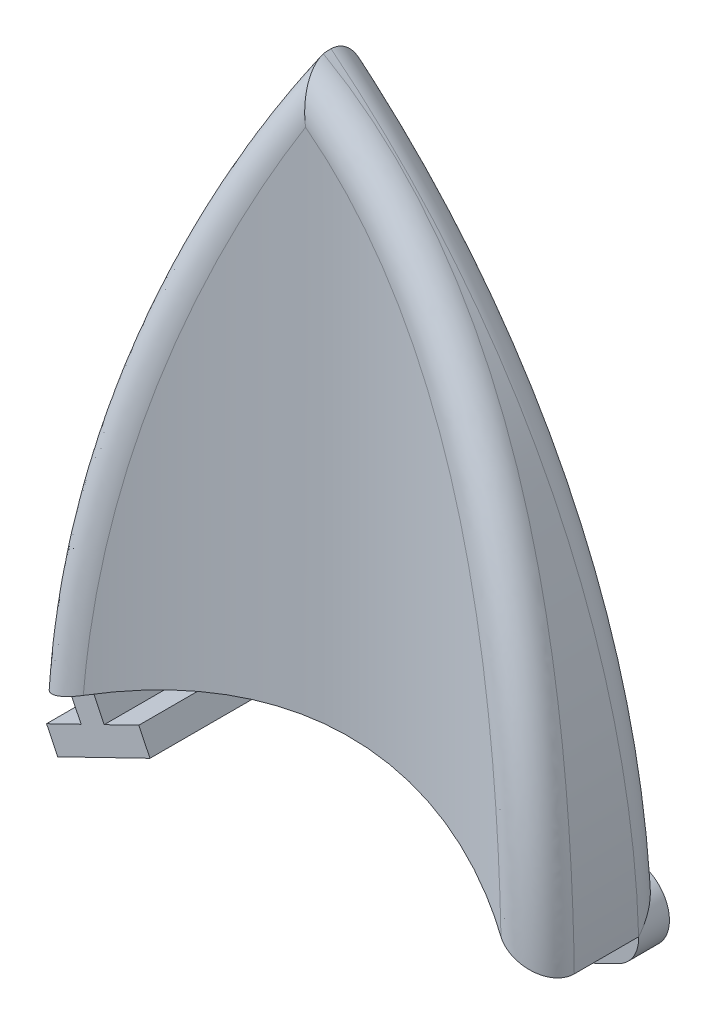
SolidWorks part; units mm, degrees
ref_plane "Plano frontal" through (0, 0, 0) normal (0, 0, 1) x (1, 0, 0)
ref_plane "Plano superior" through (0, 0, 0) normal (0, 1, 0) x (1, 0, 0)
ref_plane "Plano direito" through (0, 0, 0) normal (1, 0, 0) x (0, 0, -1)
sketch "Esboço6" plane through (0, 0, 0) normal (0, 0, 1) x (1, 0, 0)
  line L0 (0, 0) -> (0, 60.7591) construction
  line L1 (-22.0332, 45.3755) -> (14.6756, -30.2231) construction
  line L2 (42.1794, 20.4812) -> (-36.239, -17.5967) construction
  dimension "D1" = 64.1
sketch "Esboço1" plane through (0, 0, 0) normal (0, 1, 0) x (1, 0, 0)
  line L1 (-25, 0) -> (25, 0)
  line L2 (-25, 0) -> (-25, -15)
  line L3 (-25, -15) -> (25, -15)
  line L4 (25, 0) -> (25, -15)
  dimension "D2" = 15
  dimension "D1" = 50
extrude "Ressalto-extrusão1" add sketch "Esboço1" along normal blind 60
sketch "Esboço2" plane through (0, 0, 0) normal (0, 0, 1) x (1, 0, 0)
  line L1 (-5, 60) -> (-25, 60)
  line L2 (-25, 60) -> (-25, 0)
  line L3 (-25, 60) -> (25, 60) construction
  line L4 (-25, 0) -> (25, 0) construction
  arc A0 (-25, 0) -> (-5, 60) centre (88.2934, -4.4311) cw
  dimension "D1" = 113.38
  dimension "D2" = 20
extrude "Corte-extrusão1" cut sketch "Esboço2" along normal up to next and the other way through all
sketch "Esboço3" plane through (0, 0, 0) normal (0, 0, -1) x (-1, 0, 0)
  line L0 (5, 60) -> (-25, 60)
  line L1 (-25, 60) -> (-25, 0)
  arc A0 (-25, 0) -> (5, 60) centre (54.9615, -2.4808) cw
  dimension "D1" = 80
extrude "Corte-extrusão2" cut sketch "Esboço3" against normal up to next
sketch "Esboço4" plane through (0, 0, 0) normal (0, -1, 0) x (1, 0, 0)
  line L0 (-25, 15) -> (25, 15) construction
  line L2 (-25, 15) -> (25, 15)
  line L3 (-25, 0) -> (-25, 15) construction
  arc A0 (-25, 15) -> (25, 15) centre (0, 46.225) ccw
  point P3 (0, 6.225)
  dimension "D1" = 40
extrude "Corte-extrusão3" cut sketch "Esboço4" against normal blind 60
fillet "Filete1" radius 3 4 edges at (16.5926, 33.2963, 0) (9.1388, 45.3851, 7.283) (-19.2683, 31.4228, 0) (-19.8055, 29.7693, 11.4724)
sketch "Esboço5" plane through (0, 0, 0) normal (0, 0, 1) x (1, 0, 0)
  line L0 (-25, 0) -> (25, 0)
  arc A0 (-25, 0) -> (25, 0) centre (0, -48.9898) cw
  dimension "D1" = 55
extrude "Corte-extrusão4" cut sketch "Esboço5" along normal up to next
sketch "Esboço7" plane through (0, 0, 0) normal (0, 0, -1) x (-1, 0, 0)
  line L0 (-21.5017, -0.1085) -> (-14.3052, -3.6029) construction
  line L1 (-19.9729, 3.0399) -> (-12.7764, -0.4545)
  line L2 (-23.0305, -3.257) -> (-15.834, -6.7514)
  line L3 (-42.1794, 20.4812) -> (36.239, -17.5967) construction
  arc A0 (-19.9729, 3.0399) -> (-23.0305, -3.257) centre (-21.5017, -0.1085) ccw
  arc A1 (-15.834, -6.7514) -> (-12.7764, -0.4545) centre (-14.3052, -3.6029) ccw
  arc A2 (5, 60) -> (-25, 0) centre (54.9615, -2.4808) ccw construction
  point P2 (-17.9035, -1.8557)
  dimension "D1" = 7
  dimension "D2" = 8
extrude "Ressalto-extrusão2" add sketch "Esboço7" against normal blind 3
sketch "Esboço12" plane through (0, 0, 0) normal (0, 0, -1) x (-1, 0, 0)
  line L0 (24.1209, 1.3571) -> (22.3737, -2.2412)
  line L1 (22.3737, -2.2412) -> (25.747, -3.8792)
  line L2 (25.747, -3.8792) -> (24.655, -6.1281)
  line L3 (24.655, -6.1281) -> (15.6594, -1.76)
  line L4 (15.6594, -1.76) -> (16.7514, 0.4889)
  line L5 (16.7514, 0.4889) -> (20.1248, -1.1492)
  line L6 (20.1248, -1.1492) -> (21.872, 2.4491)
  line L7 (21.872, 2.4491) -> (24.1209, 1.3571)
  line L10 (-42.1794, 20.4812) -> (36.239, -17.5967) construction
  arc A1 (21.9299, 1.4491) -> (4.3614, 55.5591) centre (-88.2934, -4.4311) ccw construction
  dimension "D1" = 2.5
  dimension "D2" = 4
  dimension "D3" = 10
  dimension "D4" = 1
extrude "Ressalto-extrusão5" add sketch "Esboço12" against normal blind 10
sketch "Esboço13" plane through (0, 0, 0) normal (0, 0, -1) x (-1, 0, 0)
  circle A0 centre (-14.3052, -3.6029) radius 1.75
  arc A1 (-15.834, -6.7514) -> (-12.7764, -0.4545) centre (-14.3052, -3.6029) ccw construction
  dimension "D1" = 3.5
extrude "Corte-extrusão5" cut sketch "Esboço13" against normal up to next
